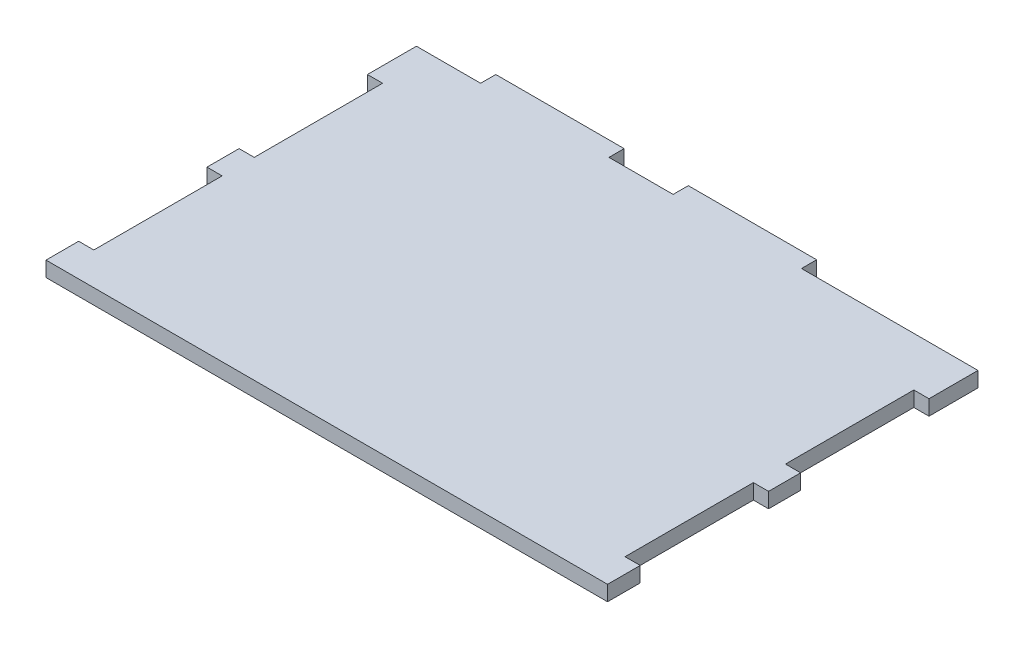
SolidWorks part; units mm, degrees
ref_plane "Front Plane" through (0, 0, 0) normal (0, 0, 1) x (1, 0, 0)
ref_plane "Top Plane" through (0, 0, 0) normal (0, 1, 0) x (1, 0, 0)
ref_plane "Right Plane" through (0, 0, 0) normal (1, 0, 0) x (0, 0, -1)
sketch "Sketch1" plane through (0, 0, 0) normal (0, 1, 0) x (1, 0, 0)
  line L0 (20.635, 36.655) -> (20.635, 39.655)
  line L1 (-55.565, -36.655) -> (55.565, -36.655)
  line L2 (-55.565, -36.655) -> (-55.565, -30.195)
  line L3 (-55.565, 36.655) -> (-42.865, 36.655)
  line L4 (55.565, -36.655) -> (55.565, -30.195)
  line L5 (-55.565, -36.655) -> (55.565, 36.655) construction
  line L6 (-55.565, 36.655) -> (55.565, -36.655) construction
  line L7 (20.635, 39.655) -> (-4.765, 39.655)
  line L8 (-4.765, 39.655) -> (-4.765, 36.655)
  line L9 (-17.465, 36.655) -> (-17.465, 39.655)
  line L10 (-17.465, 39.655) -> (-42.865, 39.655)
  line L11 (-42.865, 39.655) -> (-42.865, 36.655)
  line L12 (-17.465, 36.655) -> (-4.765, 36.655)
  line L13 (20.635, 36.655) -> (55.565, 36.655)
  line L14 (55.565, 26.955) -> (52.565, 26.955)
  line L15 (52.565, 26.955) -> (52.565, 1.555)
  line L16 (52.565, 1.555) -> (55.565, 1.555)
  line L17 (55.565, -4.795) -> (52.565, -4.795)
  line L18 (52.565, -4.795) -> (52.565, -30.195)
  line L19 (52.565, -30.195) -> (55.565, -30.195)
  line L20 (0, -36.655) -> (0, 28.6003) construction
  line L21 (55.565, 26.955) -> (55.565, 36.655)
  line L22 (55.565, -4.795) -> (55.565, 1.555)
  line L23 (-52.565, 1.555) -> (-55.565, 1.555)
  line L24 (-52.565, -30.195) -> (-55.565, -30.195)
  line L25 (-55.565, -4.795) -> (-52.565, -4.795)
  line L26 (-52.565, -4.795) -> (-52.565, -30.195)
  line L27 (-52.565, 26.955) -> (-52.565, 1.555)
  line L28 (-55.565, 26.955) -> (-52.565, 26.955)
  line L29 (-55.565, 26.955) -> (-55.565, 36.655)
  line L30 (-55.565, -4.795) -> (-55.565, 1.555)
  point P0 (0, 0)
  dimension "D1" = 111.13
  dimension "D2" = 73.31
  dimension "D3" = 34.93
  dimension "D4" = 3
  dimension "D5" = 12.7
  dimension "D6" = 25.4
  dimension "D7" = 3
  dimension "D8" = 25.4
  dimension "D9" = 3
  dimension "D10" = 9.7
  dimension "D11" = 25.4
  dimension "D12" = 6.35
  dimension "D13" = 3
  dimension "D14" = 25.4
extrude "Boss-Extrude1" add sketch "Sketch1" along normal blind 3
